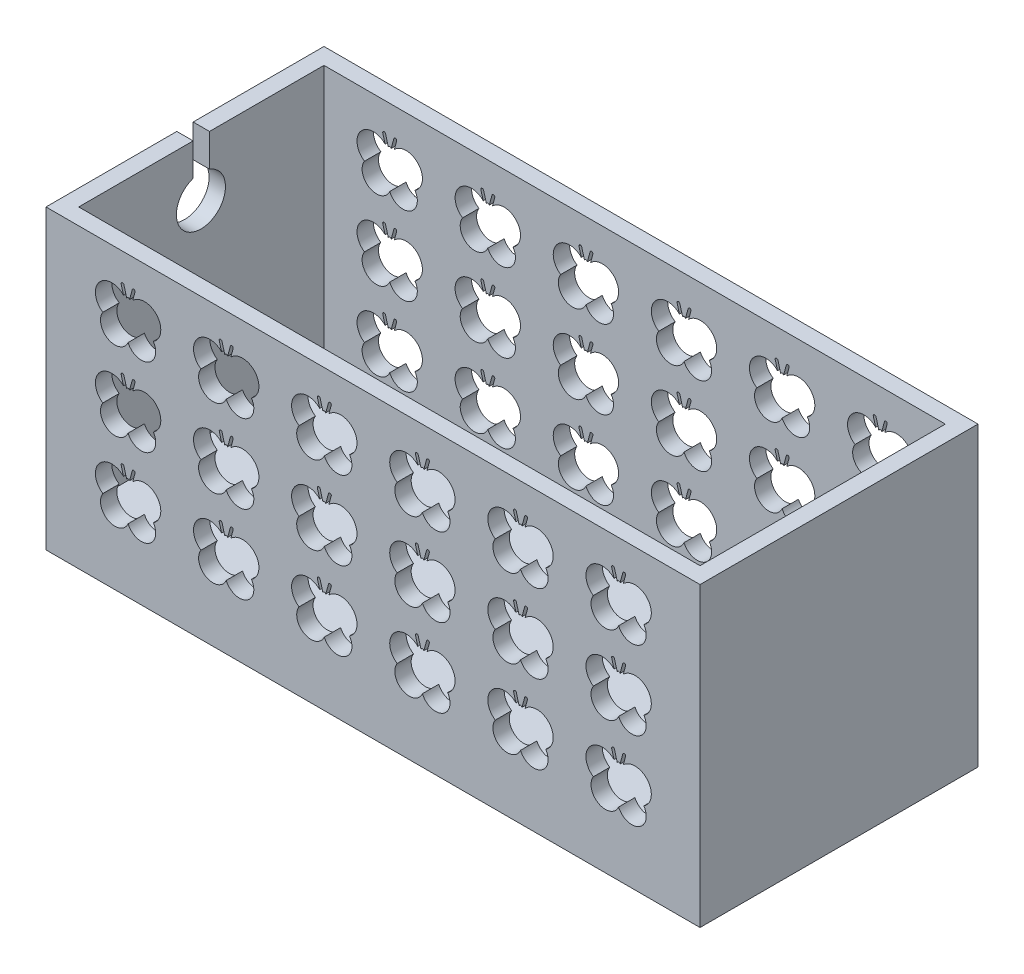
SolidWorks part; units mm, degrees
ref_plane "Front Plane" through (0, 0, 0) normal (0, 0, 1) x (1, 0, 0)
ref_plane "Top Plane" through (0, 0, 0) normal (0, 1, 0) x (1, 0, 0)
ref_plane "Right Plane" through (0, 0, 0) normal (1, 0, 0) x (0, 0, -1)
sketch "Sketch3" plane through (0, 0, 0) normal (0, 1, 0) x (1, 0, 0)
  line L1 (-63.5, -26.9875) -> (63.5, -26.9875)
  line L2 (-63.5, -26.9875) -> (-63.5, 26.9875)
  line L3 (-63.5, 26.9875) -> (63.5, 26.9875)
  line L4 (63.5, -26.9875) -> (63.5, 26.9875)
  line L5 (-63.5, -26.9875) -> (63.5, 26.9875) construction
  line L6 (-63.5, 26.9875) -> (63.5, -26.9875) construction
  point P1 (0, 0)
  dimension "D1" = 127
  dimension "D2" = 53.975
extrude "Boss-Extrude1" add sketch "Sketch3" along normal blind 53.975
sketch "Sketch4" plane through (0, 53.975, 0) normal (0, 1, 0) x (1, 0, 0)
  line L0 (-63.5, 26.9875) -> (-63.5, -26.9875) construction
  line L1 (-60.325, -23.8125) -> (60.325, -23.8125)
  line L2 (-60.325, -23.8125) -> (-60.325, 23.8125)
  line L3 (-60.325, 23.8125) -> (60.325, 23.8125)
  line L4 (60.325, -23.8125) -> (60.325, 23.8125)
  line L5 (-60.325, -23.8125) -> (60.325, 23.8125) construction
  line L6 (-60.325, 23.8125) -> (60.325, -23.8125) construction
  line L7 (63.5, 26.9875) -> (-63.5, 26.9875) construction
  line L8 (63.5, -26.9875) -> (63.5, 26.9875) construction
  line L9 (-63.5, -26.9875) -> (63.5, -26.9875) construction
  point P0 (0, 0)
  dimension "D1" = 3.175
  dimension "D2" = 3.175
  dimension "D3" = 3.175
  dimension "D4" = 3.175
extrude "Cut-Extrude2" cut sketch "Sketch4" against normal blind 50.8
sketch "Sketch8" plane through (-63.5, 0, 0) normal (-1, 0, 0) x (0, 0, 1)
  line L1 (-1.5875, 66.675) -> (1.5875, 66.675)
  line L2 (-1.5875, 66.675) -> (-1.5875, 47.625)
  line L4 (1.5875, 66.675) -> (1.5875, 47.6816)
  arc A0 (-1.5875, 47.625) -> (1.5875, 47.6816) centre (0.08, 43.164) ccw
  point P0 (0, 53.975)
  point P1 (1.5875, 53.975)
  point P3 (-1.5875, 53.975)
  point P7 (-1.5875, 53.975)
extrude "Cut-Extrude3" cut sketch "Sketch8" against normal blind 3.175
sketch "Sketch9" plane through (0, 0, 26.9875) normal (0, 0, 1) x (1, 0, 0)
  line L0 (-28.2324, 46.5072) -> (-27.6943, 48.468)
  line L1 (-27.6145, 46.6589) -> (-27.1583, 48.321)
  line L2 (-28.7852, 46.5072) -> (-29.3232, 48.468)
  line L3 (-29.4031, 46.6589) -> (-29.8592, 48.321)
  line L4 (-9.1824, 46.5072) -> (-8.6443, 48.468)
  line L5 (-8.5645, 46.6589) -> (-8.1083, 48.321)
  line L6 (-47.2824, 46.5072) -> (-46.7443, 48.468)
  line L7 (-46.6645, 46.6589) -> (-46.2083, 48.321)
  line L8 (-9.7352, 46.5072) -> (-10.2732, 48.468)
  line L9 (-47.8352, 46.5072) -> (-48.3732, 48.468)
  line L10 (-48.4531, 46.6589) -> (-48.9092, 48.321)
  line L11 (-10.3531, 46.6589) -> (-10.8092, 48.321)
  line L12 (9.8676, 46.5072) -> (10.4057, 48.468)
  line L13 (10.4855, 46.6589) -> (10.9417, 48.321)
  line L14 (9.3148, 46.5072) -> (8.7768, 48.468)
  line L15 (8.6969, 46.6589) -> (8.2408, 48.321)
  line L16 (28.9176, 46.5072) -> (29.4557, 48.468)
  line L17 (29.5355, 46.6589) -> (29.9917, 48.321)
  line L18 (28.3648, 46.5072) -> (27.8268, 48.468)
  line L19 (27.7469, 46.6589) -> (27.2908, 48.321)
  line L20 (47.9676, 46.5072) -> (48.5057, 48.468)
  line L21 (48.5855, 46.6589) -> (49.0417, 48.321)
  line L22 (47.4148, 46.5072) -> (46.8768, 48.468)
  line L23 (46.7969, 46.6589) -> (46.3408, 48.321)
  line L24 (-28.2324, 31.2672) -> (-27.6943, 33.228)
  line L25 (-27.6145, 31.4189) -> (-27.1583, 33.081)
  line L26 (-28.7852, 31.2672) -> (-29.3232, 33.228)
  line L27 (-29.4031, 31.4189) -> (-29.8592, 33.081)
  line L28 (-9.1824, 31.2672) -> (-8.6443, 33.228)
  line L29 (-8.5645, 31.4189) -> (-8.1083, 33.081)
  line L30 (-9.7352, 31.2672) -> (-10.2732, 33.228)
  line L31 (-10.3531, 31.4189) -> (-10.8092, 33.081)
  line L32 (9.8676, 31.2672) -> (10.4057, 33.228)
  line L33 (10.4855, 31.4189) -> (10.9417, 33.081)
  line L34 (9.3148, 31.2672) -> (8.7768, 33.228)
  line L35 (8.6969, 31.4189) -> (8.2408, 33.081)
  line L36 (28.9176, 31.2672) -> (29.4557, 33.228)
  line L37 (29.5355, 31.4189) -> (29.9917, 33.081)
  line L38 (28.3648, 31.2672) -> (27.8268, 33.228)
  line L39 (27.7469, 31.4189) -> (27.2908, 33.081)
  line L40 (47.9676, 31.2672) -> (48.5057, 33.228)
  line L41 (48.5855, 31.4189) -> (49.0417, 33.081)
  line L42 (47.4148, 31.2672) -> (46.8768, 33.228)
  line L43 (46.7969, 31.4189) -> (46.3408, 33.081)
  line L44 (-28.2324, 16.0272) -> (-27.6943, 17.988)
  line L45 (-27.6145, 16.1789) -> (-27.1583, 17.841)
  line L46 (-28.7852, 16.0272) -> (-29.3232, 17.988)
  line L47 (-29.4031, 16.1789) -> (-29.8592, 17.841)
  line L48 (-9.1824, 16.0272) -> (-8.6443, 17.988)
  line L49 (-8.5645, 16.1789) -> (-8.1083, 17.841)
  line L50 (-9.7352, 16.0272) -> (-10.2732, 17.988)
  line L51 (-10.3531, 16.1789) -> (-10.8092, 17.841)
  line L52 (9.8676, 16.0272) -> (10.4057, 17.988)
  line L53 (10.4855, 16.1789) -> (10.9417, 17.841)
  line L54 (9.3148, 16.0272) -> (8.7768, 17.988)
  line L55 (8.6969, 16.1789) -> (8.2408, 17.841)
  line L56 (28.9176, 16.0272) -> (29.4557, 17.988)
  line L57 (29.5355, 16.1789) -> (29.9917, 17.841)
  line L58 (28.3648, 16.0272) -> (27.8268, 17.988)
  line L59 (27.7469, 16.1789) -> (27.2908, 17.841)
  line L60 (47.9676, 16.0272) -> (48.5057, 17.988)
  line L61 (48.5855, 16.1789) -> (49.0417, 17.841)
  line L62 (47.4148, 16.0272) -> (46.8768, 17.988)
  line L63 (46.7969, 16.1789) -> (46.3408, 17.841)
  line L64 (-47.2824, 31.2672) -> (-46.7443, 33.228)
  line L65 (-46.6645, 31.4189) -> (-46.2083, 33.081)
  line L66 (-47.8352, 31.2672) -> (-48.3732, 33.228)
  line L67 (-48.4531, 31.4189) -> (-48.9092, 33.081)
  line L68 (-47.2824, 16.0272) -> (-46.7443, 17.988)
  line L69 (-46.6645, 16.1789) -> (-46.2083, 17.841)
  line L70 (-47.8352, 16.0272) -> (-48.3732, 17.988)
  line L71 (-48.4531, 16.1789) -> (-48.9092, 17.841)
  arc A0 (-48.4531, 46.6589) -> (-52.4597, 41.7851) centre (-50.7338, 44.45) ccw
  arc A1 (-52.4597, 41.7851) -> (-47.5588, 39.1461) centre (-50.1258, 40.2491) ccw
  arc A2 (-42.6578, 41.7851) -> (-47.5588, 39.1461) centre (-44.9917, 40.2491) cw
  arc A3 (-46.6645, 46.6589) -> (-42.6578, 41.7851) centre (-44.3838, 44.45) cw
  arc A4 (-47.2824, 46.5072) -> (-47.8352, 46.5072) centre (-47.5588, 46.4222) ccw
  arc A5 (-46.2083, 48.321) -> (-46.7443, 48.468) centre (-46.4763, 48.3945) ccw
  arc A6 (-29.4031, 46.6589) -> (-33.4097, 41.7851) centre (-31.6838, 44.45) ccw
  arc A7 (-48.9092, 48.321) -> (-48.3732, 48.468) centre (-48.6412, 48.3945) cw
  arc A8 (-33.4097, 41.7851) -> (-28.5088, 39.1461) centre (-31.0758, 40.2491) ccw
  arc A9 (-23.6078, 41.7851) -> (-28.5088, 39.1461) centre (-25.9417, 40.2491) cw
  arc A10 (-27.6145, 46.6589) -> (-23.6078, 41.7851) centre (-25.3338, 44.45) cw
  arc A11 (-28.2324, 46.5072) -> (-28.7852, 46.5072) centre (-28.5088, 46.4222) ccw
  arc A12 (-27.1583, 48.321) -> (-27.6943, 48.468) centre (-27.4263, 48.3945) ccw
  arc A13 (-29.8592, 48.321) -> (-29.3232, 48.468) centre (-29.5912, 48.3945) cw
  arc A14 (-10.3531, 46.6589) -> (-14.3597, 41.7851) centre (-12.6338, 44.45) ccw
  arc A15 (-14.3597, 41.7851) -> (-9.4588, 39.1461) centre (-12.0258, 40.2491) ccw
  arc A16 (-4.5578, 41.7851) -> (-9.4588, 39.1461) centre (-6.8917, 40.2491) cw
  arc A18 (-8.5645, 46.6589) -> (-4.5578, 41.7851) centre (-6.2838, 44.45) cw
  arc A19 (-9.1824, 46.5072) -> (-9.7352, 46.5072) centre (-9.4588, 46.4222) ccw
  arc A20 (-8.1083, 48.321) -> (-8.6443, 48.468) centre (-8.3763, 48.3945) ccw
  arc A21 (-10.8092, 48.321) -> (-10.2732, 48.468) centre (-10.5412, 48.3945) cw
  arc A22 (8.6969, 46.6589) -> (4.6903, 41.7851) centre (6.4162, 44.45) ccw
  arc A23 (4.6903, 41.7851) -> (9.5912, 39.1461) centre (7.0242, 40.2491) ccw
  arc A24 (14.4922, 41.7851) -> (9.5912, 39.1461) centre (12.1583, 40.2491) cw
  arc A25 (10.4855, 46.6589) -> (14.4922, 41.7851) centre (12.7662, 44.45) cw
  arc A26 (9.8676, 46.5072) -> (9.3148, 46.5072) centre (9.5912, 46.4222) ccw
  arc A27 (10.9417, 48.321) -> (10.4057, 48.468) centre (10.6737, 48.3945) ccw
  arc A28 (8.2408, 48.321) -> (8.7768, 48.468) centre (8.5088, 48.3945) cw
  arc A29 (27.7469, 46.6589) -> (23.7403, 41.7851) centre (25.4662, 44.45) ccw
  arc A30 (23.7403, 41.7851) -> (28.6412, 39.1461) centre (26.0742, 40.2491) ccw
  arc A31 (33.5422, 41.7851) -> (28.6412, 39.1461) centre (31.2083, 40.2491) cw
  arc A32 (29.5355, 46.6589) -> (33.5422, 41.7851) centre (31.8162, 44.45) cw
  arc A33 (28.9176, 46.5072) -> (28.3648, 46.5072) centre (28.6412, 46.4222) ccw
  arc A34 (29.9917, 48.321) -> (29.4557, 48.468) centre (29.7237, 48.3945) ccw
  arc A35 (27.2908, 48.321) -> (27.8268, 48.468) centre (27.5588, 48.3945) cw
  arc A36 (46.7969, 46.6589) -> (42.7903, 41.7851) centre (44.5162, 44.45) ccw
  arc A37 (42.7903, 41.7851) -> (47.6912, 39.1461) centre (45.1242, 40.2491) ccw
  arc A38 (52.5922, 41.7851) -> (47.6912, 39.1461) centre (50.2583, 40.2491) cw
  arc A39 (48.5855, 46.6589) -> (52.5922, 41.7851) centre (50.8662, 44.45) cw
  arc A40 (47.9676, 46.5072) -> (47.4148, 46.5072) centre (47.6912, 46.4222) ccw
  arc A41 (49.0417, 48.321) -> (48.5057, 48.468) centre (48.7737, 48.3945) ccw
  arc A42 (46.3408, 48.321) -> (46.8768, 48.468) centre (46.6088, 48.3945) cw
  arc A43 (-29.4031, 31.4189) -> (-33.4097, 26.5451) centre (-31.6838, 29.21) ccw
  arc A44 (-33.4097, 26.5451) -> (-28.5088, 23.9061) centre (-31.0758, 25.0091) ccw
  arc A45 (-23.6078, 26.5451) -> (-28.5088, 23.9061) centre (-25.9417, 25.0091) cw
  arc A46 (-27.6145, 31.4189) -> (-23.6078, 26.5451) centre (-25.3338, 29.21) cw
  arc A47 (-28.2324, 31.2672) -> (-28.7852, 31.2672) centre (-28.5088, 31.1822) ccw
  arc A48 (-27.1583, 33.081) -> (-27.6943, 33.228) centre (-27.4263, 33.1545) ccw
  arc A49 (-29.8592, 33.081) -> (-29.3232, 33.228) centre (-29.5912, 33.1545) cw
  arc A50 (-10.3531, 31.4189) -> (-14.3597, 26.5451) centre (-12.6338, 29.21) ccw
  arc A51 (-14.3597, 26.5451) -> (-9.4588, 23.9061) centre (-12.0258, 25.0091) ccw
  arc A52 (-4.5578, 26.5451) -> (-9.4588, 23.9061) centre (-6.8917, 25.0091) cw
  arc A53 (-8.5645, 31.4189) -> (-4.5578, 26.5451) centre (-6.2838, 29.21) cw
  arc A54 (-9.1824, 31.2672) -> (-9.7352, 31.2672) centre (-9.4588, 31.1822) ccw
  arc A55 (-8.1083, 33.081) -> (-8.6443, 33.228) centre (-8.3763, 33.1545) ccw
  arc A56 (-10.8092, 33.081) -> (-10.2732, 33.228) centre (-10.5412, 33.1545) cw
  arc A57 (8.6969, 31.4189) -> (4.6903, 26.5451) centre (6.4162, 29.21) ccw
  arc A58 (4.6903, 26.5451) -> (9.5912, 23.9061) centre (7.0242, 25.0091) ccw
  arc A59 (14.4922, 26.5451) -> (9.5912, 23.9061) centre (12.1583, 25.0091) cw
  arc A60 (10.4855, 31.4189) -> (14.4922, 26.5451) centre (12.7662, 29.21) cw
  arc A61 (9.8676, 31.2672) -> (9.3148, 31.2672) centre (9.5912, 31.1822) ccw
  arc A62 (10.9417, 33.081) -> (10.4057, 33.228) centre (10.6737, 33.1545) ccw
  arc A63 (8.2408, 33.081) -> (8.7768, 33.228) centre (8.5088, 33.1545) cw
  arc A64 (27.7469, 31.4189) -> (23.7403, 26.5451) centre (25.4662, 29.21) ccw
  arc A65 (23.7403, 26.5451) -> (28.6412, 23.9061) centre (26.0742, 25.0091) ccw
  arc A66 (33.5422, 26.5451) -> (28.6412, 23.9061) centre (31.2083, 25.0091) cw
  arc A67 (29.5355, 31.4189) -> (33.5422, 26.5451) centre (31.8162, 29.21) cw
  arc A68 (28.9176, 31.2672) -> (28.3648, 31.2672) centre (28.6412, 31.1822) ccw
  arc A69 (29.9917, 33.081) -> (29.4557, 33.228) centre (29.7237, 33.1545) ccw
  arc A70 (27.2908, 33.081) -> (27.8268, 33.228) centre (27.5588, 33.1545) cw
  arc A71 (46.7969, 31.4189) -> (42.7903, 26.5451) centre (44.5162, 29.21) ccw
  arc A72 (42.7903, 26.5451) -> (47.6912, 23.9061) centre (45.1242, 25.0091) ccw
  arc A73 (52.5922, 26.5451) -> (47.6912, 23.9061) centre (50.2583, 25.0091) cw
  arc A74 (48.5855, 31.4189) -> (52.5922, 26.5451) centre (50.8662, 29.21) cw
  arc A75 (47.9676, 31.2672) -> (47.4148, 31.2672) centre (47.6912, 31.1822) ccw
  arc A76 (49.0417, 33.081) -> (48.5057, 33.228) centre (48.7737, 33.1545) ccw
  arc A77 (46.3408, 33.081) -> (46.8768, 33.228) centre (46.6088, 33.1545) cw
  arc A78 (-29.4031, 16.1789) -> (-33.4097, 11.3051) centre (-31.6838, 13.97) ccw
  arc A79 (-33.4097, 11.3051) -> (-28.5088, 8.6661) centre (-31.0758, 9.7691) ccw
  arc A80 (-23.6078, 11.3051) -> (-28.5088, 8.6661) centre (-25.9417, 9.7691) cw
  arc A81 (-27.6145, 16.1789) -> (-23.6078, 11.3051) centre (-25.3338, 13.97) cw
  arc A82 (-28.2324, 16.0272) -> (-28.7852, 16.0272) centre (-28.5088, 15.9422) ccw
  arc A83 (-27.1583, 17.841) -> (-27.6943, 17.988) centre (-27.4263, 17.9145) ccw
  arc A84 (-29.8592, 17.841) -> (-29.3232, 17.988) centre (-29.5912, 17.9145) cw
  arc A85 (-10.3531, 16.1789) -> (-14.3597, 11.3051) centre (-12.6338, 13.97) ccw
  arc A86 (-14.3597, 11.3051) -> (-9.4588, 8.6661) centre (-12.0258, 9.7691) ccw
  arc A87 (-4.5578, 11.3051) -> (-9.4588, 8.6661) centre (-6.8917, 9.7691) cw
  arc A88 (-8.5645, 16.1789) -> (-4.5578, 11.3051) centre (-6.2838, 13.97) cw
  arc A89 (-9.1824, 16.0272) -> (-9.7352, 16.0272) centre (-9.4588, 15.9422) ccw
  arc A90 (-8.1083, 17.841) -> (-8.6443, 17.988) centre (-8.3763, 17.9145) ccw
  arc A91 (-10.8092, 17.841) -> (-10.2732, 17.988) centre (-10.5412, 17.9145) cw
  arc A92 (8.6969, 16.1789) -> (4.6903, 11.3051) centre (6.4162, 13.97) ccw
  arc A93 (4.6903, 11.3051) -> (9.5912, 8.6661) centre (7.0242, 9.7691) ccw
  arc A94 (14.4922, 11.3051) -> (9.5912, 8.6661) centre (12.1583, 9.7691) cw
  arc A95 (10.4855, 16.1789) -> (14.4922, 11.3051) centre (12.7662, 13.97) cw
  arc A96 (9.8676, 16.0272) -> (9.3148, 16.0272) centre (9.5912, 15.9422) ccw
  arc A97 (10.9417, 17.841) -> (10.4057, 17.988) centre (10.6737, 17.9145) ccw
  arc A98 (8.2408, 17.841) -> (8.7768, 17.988) centre (8.5088, 17.9145) cw
  arc A99 (27.7469, 16.1789) -> (23.7403, 11.3051) centre (25.4662, 13.97) ccw
  arc A100 (23.7403, 11.3051) -> (28.6412, 8.6661) centre (26.0742, 9.7691) ccw
  arc A101 (33.5422, 11.3051) -> (28.6412, 8.6661) centre (31.2083, 9.7691) cw
  arc A102 (29.5355, 16.1789) -> (33.5422, 11.3051) centre (31.8162, 13.97) cw
  arc A103 (28.9176, 16.0272) -> (28.3648, 16.0272) centre (28.6412, 15.9422) ccw
  arc A104 (29.9917, 17.841) -> (29.4557, 17.988) centre (29.7237, 17.9145) ccw
  arc A105 (27.2908, 17.841) -> (27.8268, 17.988) centre (27.5588, 17.9145) cw
  arc A106 (46.7969, 16.1789) -> (42.7903, 11.3051) centre (44.5162, 13.97) ccw
  arc A107 (42.7903, 11.3051) -> (47.6912, 8.6661) centre (45.1242, 9.7691) ccw
  arc A108 (52.5922, 11.3051) -> (47.6912, 8.6661) centre (50.2583, 9.7691) cw
  arc A109 (48.5855, 16.1789) -> (52.5922, 11.3051) centre (50.8662, 13.97) cw
  arc A110 (47.9676, 16.0272) -> (47.4148, 16.0272) centre (47.6912, 15.9422) ccw
  arc A111 (49.0417, 17.841) -> (48.5057, 17.988) centre (48.7737, 17.9145) ccw
  arc A112 (46.3408, 17.841) -> (46.8768, 17.988) centre (46.6088, 17.9145) cw
  arc A113 (-48.4531, 31.4189) -> (-52.4597, 26.5451) centre (-50.7338, 29.21) ccw
  arc A114 (-52.4597, 26.5451) -> (-47.5588, 23.9061) centre (-50.1258, 25.0091) ccw
  arc A115 (-42.6578, 26.5451) -> (-47.5588, 23.9061) centre (-44.9917, 25.0091) cw
  arc A116 (-46.6645, 31.4189) -> (-42.6578, 26.5451) centre (-44.3838, 29.21) cw
  arc A117 (-47.2824, 31.2672) -> (-47.8352, 31.2672) centre (-47.5588, 31.1822) ccw
  arc A118 (-46.2083, 33.081) -> (-46.7443, 33.228) centre (-46.4763, 33.1545) ccw
  arc A119 (-48.9092, 33.081) -> (-48.3732, 33.228) centre (-48.6412, 33.1545) cw
  arc A120 (-48.4531, 16.1789) -> (-52.4597, 11.3051) centre (-50.7338, 13.97) ccw
  arc A121 (-52.4597, 11.3051) -> (-47.5588, 8.6661) centre (-50.1258, 9.7691) ccw
  arc A122 (-42.6578, 11.3051) -> (-47.5588, 8.6661) centre (-44.9917, 9.7691) cw
  arc A123 (-46.6645, 16.1789) -> (-42.6578, 11.3051) centre (-44.3838, 13.97) cw
  arc A124 (-47.2824, 16.0272) -> (-47.8352, 16.0272) centre (-47.5588, 15.9422) ccw
  arc A125 (-46.2083, 17.841) -> (-46.7443, 17.988) centre (-46.4763, 17.9145) ccw
  arc A126 (-48.9092, 17.841) -> (-48.3732, 17.988) centre (-48.6412, 17.9145) cw
  point P2 (0, 0)
  point P7 (-47.0175, 46.4222)
  point P9 (-27.9675, 46.4222)
  point P19 (-47.5588, 45.5756)
  point P23 (-48.1, 46.4222)
  point P37 (-28.5088, 45.5756)
  point P41 (-29.05, 46.4222)
  point P51 (-8.9175, 46.4222)
  point P60 (-9.4588, 45.5756)
  point P64 (-10, 46.4222)
  point P74 (10.1325, 46.4222)
  point P83 (9.5912, 45.5756)
  point P87 (9.05, 46.4222)
  point P97 (29.1825, 46.4222)
  point P106 (28.6412, 45.5756)
  point P110 (28.1, 46.4222)
  point P120 (48.2325, 46.4222)
  point P129 (47.6912, 45.5756)
  point P133 (47.15, 46.4222)
  point P143 (-27.9675, 31.1822)
  point P152 (-28.5088, 30.3356)
  point P156 (-29.05, 31.1822)
  point P166 (-8.9175, 31.1822)
  point P175 (-9.4588, 30.3356)
  point P179 (-10, 31.1822)
  point P189 (10.1325, 31.1822)
  point P198 (9.5912, 30.3356)
  point P202 (9.05, 31.1822)
  point P212 (29.1825, 31.1822)
  point P221 (28.6412, 30.3356)
  point P225 (28.1, 31.1822)
  point P235 (48.2325, 31.1822)
  point P244 (47.6912, 30.3356)
  point P248 (47.15, 31.1822)
  point P258 (-27.9675, 15.9422)
  point P267 (-28.5088, 15.0956)
  point P271 (-29.05, 15.9422)
  point P281 (-8.9175, 15.9422)
  point P290 (-9.4588, 15.0956)
  point P294 (-10, 15.9422)
  point P304 (10.1325, 15.9422)
  point P313 (9.5912, 15.0956)
  point P317 (9.05, 15.9422)
  point P327 (29.1825, 15.9422)
  point P336 (28.6412, 15.0956)
  point P340 (28.1, 15.9422)
  point P350 (48.2325, 15.9422)
  point P359 (47.6912, 15.0956)
  point P363 (47.15, 15.9422)
  point P373 (-47.0175, 31.1822)
  point P382 (-47.5588, 30.3356)
  point P386 (-48.1, 31.1822)
  point P396 (-47.0175, 15.9422)
  point P405 (-47.5588, 15.0956)
  point P409 (-48.1, 15.9422)
  dimension "D2" = 3
  dimension "D1" = 6
extrude "Cut-Extrude7" cut sketch "Sketch9" against normal through all
sketch "Sketch13" plane through (0, 0, 0) normal (0, -1, 0) x (1, 0, 0)
  line L1 (63.5, -26.9875) -> (-63.5, -26.9875)
  line L2 (63.5, -26.9875) -> (63.5, 26.9875)
  line L3 (63.5, 26.9875) -> (-63.5, 26.9875)
  line L4 (-63.5, -26.9875) -> (-63.5, 26.9875)
  line L5 (63.5, -26.9875) -> (-63.5, 26.9875) construction
  line L6 (63.5, 26.9875) -> (-63.5, -26.9875) construction
  point P0 (0, 0)
  dimension "D1" = 53.975
  dimension "D2" = 127
extrude "Boss-Extrude2" add sketch "Sketch13" along normal blind 3.7032
sketch "Sketch14" plane through (0, 3.175, 0) normal (0, 1, 0) x (1, 0, 0)
  line L0 (-60.325, -23.8125) -> (60.325, -23.8125) construction
  line L1 (60.325, 23.8125) -> (-60.325, 23.8125) construction
  line L2 (60.325, 23.8125) -> (-60.325, 23.8125) construction
  line L5 (63.5, -26.9875) -> (63.5, 26.9875) construction
  line L6 (-63.5, -26.9875) -> (-63.5, 26.9875) construction
  circle A0 centre (-31.75, 8) radius 2.9845
  circle A1 centre (-31.75, -8) radius 2.9845
  circle A2 centre (34.925, 8) radius 2.9845
  circle A3 centre (34.925, -8) radius 2.9845
  dimension "D1" = 5.969
  dimension "D3" = 5.969
  dimension "D9" = 16
  dimension "D10" = 28.575
  dimension "D2" = 47.625
  dimension "D4" = 16
  dimension "D5" = 15.8125
  dimension "D6" = 15.8125
  dimension "D7" = 31.75
  dimension "D8" = 2
extrude "Cut-Extrude9" cut sketch "Sketch14" against normal blind 3.81
sketch "Sketch16" plane through (0, -0.635, 0) normal (0, 1, 0) x (1, 0, 0)
  circle A0 centre (-31.75, 8) radius 1.905
  circle A1 centre (-31.75, -8) radius 1.905
  circle A2 centre (34.925, -8) radius 1.905
  circle A3 centre (34.925, 8) radius 1.905
  point P0 (-31.75, 8)
  point P2 (-31.75, -8)
  point P3 (34.925, 8)
  point P6 (34.925, -8)
  point P9 (34.925, 8)
  point P11 (0, 0)
  dimension "D1" = 3.81
  dimension "D2" = 3.81
  dimension "D3" = 3.81
  dimension "D4" = 3.81
extrude "Cut-Extrude11" cut sketch "Sketch16" against normal blind 25.4
